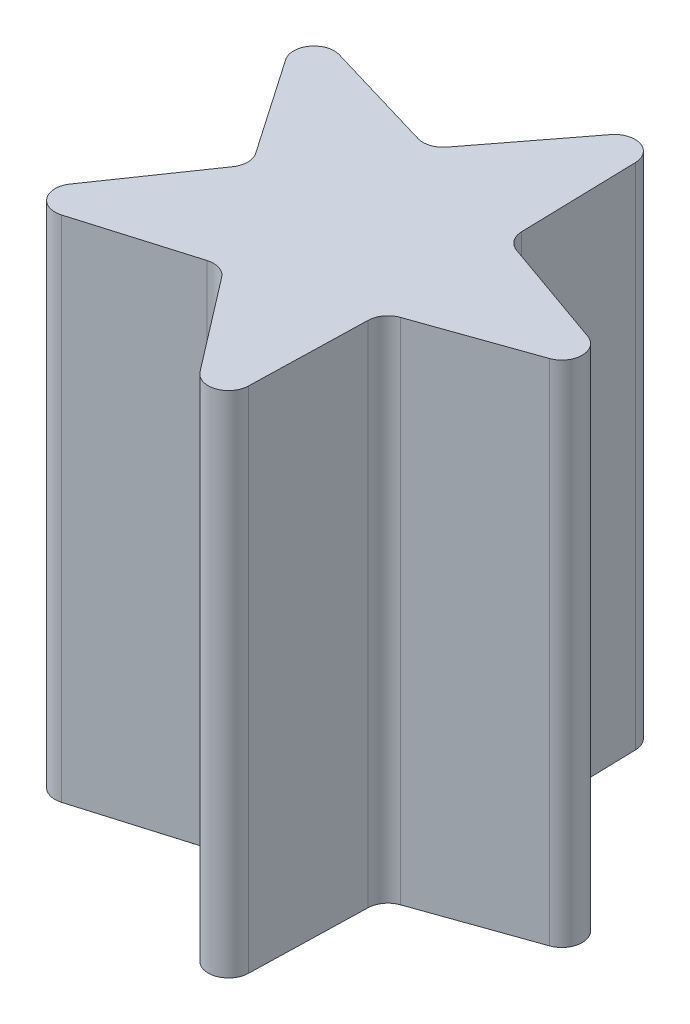
SolidWorks part; units mm, degrees
ref_plane "Front Plane" through (0, 0, 0) normal (0, 0, 1) x (1, 0, 0)
ref_plane "Top Plane" through (0, 0, 0) normal (0, 1, 0) x (1, 0, 0)
ref_plane "Right Plane" through (0, 0, 0) normal (1, 0, 0) x (0, 0, -1)
sketch "Sketch2" plane through (0, 0, 0) normal (0, 1, 0) x (1, 0, 0)
  line L0 (-3.4494, 0) -> (6.7353, 31.3452)
  line L26 (-3.4494, 0) -> (29.5089, 0)
  line L27 (-3.4494, 0) -> (6.7353, -31.3452)
  line L28 (-3.4494, 0) -> (-30.1132, -19.3724)
  line L29 (-30.1132, 19.3724) -> (-3.4494, 0)
  line L30 (-30.1132, -19.3724) -> (-16.7813, 0)
  line L31 (-16.7813, 0) -> (-7.5692, -12.6794)
  line L32 (-7.5692, -12.6794) -> (7.3363, -7.8363)
  line L33 (7.3363, -7.8363) -> (7.3363, 7.8363)
  line L34 (7.3363, 7.8363) -> (-7.5692, 12.6794)
  line L35 (-7.5692, 12.6794) -> (-16.7813, 0)
  line L36 (-16.7813, 0) -> (-30.1132, 19.3724)
  line L37 (-30.1132, 19.3724) -> (-7.5692, 12.6794)
  line L38 (-7.5692, 12.6794) -> (6.7353, 31.3452)
  line L39 (6.7353, 31.3452) -> (7.3363, 7.8363)
  line L40 (29.5089, 0) -> (7.3363, 7.8363)
  line L41 (29.5089, 0) -> (7.3363, -7.8363)
  line L42 (7.3363, -7.8363) -> (6.7353, -31.3452)
  line L43 (6.7353, -31.3452) -> (-7.5692, -12.6794)
  line L44 (-7.5692, -12.6794) -> (-30.1132, -19.3724)
  circle A1 centre (-3.4494, 0) radius 10.7857 construction
  point P0 (0, 0)
extrude "Boss-Extrude2" add sketch "Sketch2" along normal blind 63.5 and the other way blind 0.0001 contours L26 L40 L33 | L41 L26 L33 | L32 L33 L26 L27 | L33 L34 L0 L26 | L34 L35 L29 L0 | L29 L35 L31 L28 | L31 L32 L27 L28 | L43 L27 L32 | L42 L32 L27 | L44 L31 L28 | L31 L30 L28 | L36 L35 L29 | L37 L29 L35 | L38 L34 L0 | L39 L0 L34
fillet "Fillet2" radius 2.54 10 edges at (-30.1132, 31.7499, 19.3724) (-16.7813, 31.7499, 0) (-30.1132, 31.7499, -19.3724) (-7.5692, 31.7499, -12.6794) (6.7353, 31.7499, -31.3452) (7.3363, 31.7499, -7.8363) (29.5089, 31.7499, 0) (-7.5692, 31.7499, 12.6794) (7.3363, 31.7499, 7.8363) (6.7353, 31.7499, 31.3452)
